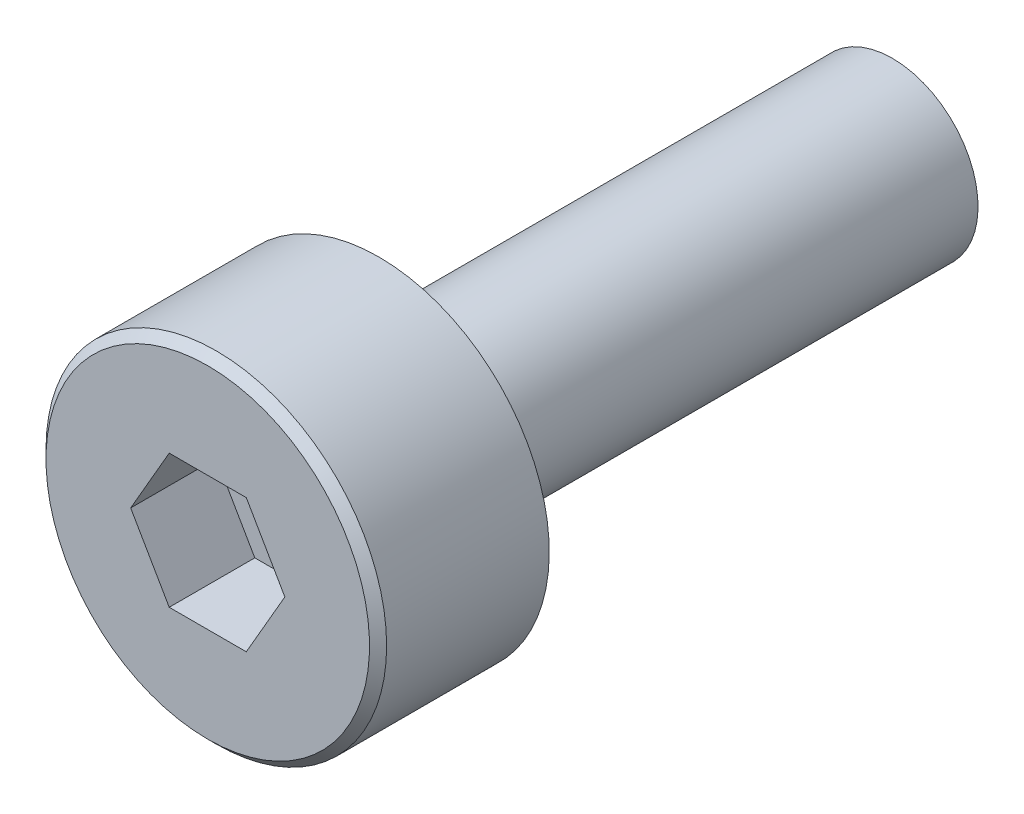
SolidWorks part; units mm, degrees
material "普通碳钢"
ref_plane "前视基准面" through (0, 0, 0) normal (0, 0, 1) x (1, 0, 0)
ref_plane "上视基准面" through (0, 0, 0) normal (0, 1, 0) x (1, 0, 0)
ref_plane "右视基准面" through (0, 0, 0) normal (1, 0, 0) x (0, 0, -1)
sketch "草图1" plane through (0, 0, 0) normal (1, 0, 0) x (0, 0, -1)
  line L0 (0, 0) -> (0, 1.99)
  line L1 (0, 1.99) -> (2, 1.99)
  line L2 (2, 1.99) -> (2, 1)
  line L3 (2, 1) -> (8, 1)
  line L4 (8, 1) -> (8, 0)
  line L5 (8, 0) -> (0, 0) construction
  line L6 (0, 0) -> (8, 0)
  dimension "D1" = 3.98
  dimension "D2" = 2
  dimension "D3" = 2
  dimension "D4" = 6
revolve "旋转1" add sketch "草图1" angle 360 about L5
cosmetic thread "装饰螺纹线1" parameters "D2"=1.221
sketch "草图2" plane through (0, 0, 0) normal (0, 0, 1) x (1, 0, 0)
  line L1 (0.4503, 0.78) -> (-0.4503, 0.78)
  line L2 (-0.4503, 0.78) -> (-0.9007, 0)
  line L3 (-0.9007, 0) -> (-0.4503, -0.78)
  line L4 (-0.4503, -0.78) -> (0.4503, -0.78)
  line L5 (0.4503, -0.78) -> (0.9007, 0)
  line L6 (0.9007, 0) -> (0.4503, 0.78)
  circle A0 centre (0, 0) radius 0.78 construction
  dimension "D1" = 1.56
extrude "切除-拉伸1" cut sketch "草图2" against normal blind 1
chamfer "装饰倒角" distance 0.1 angle 45 1 edges at (0, 1.99, 0)
